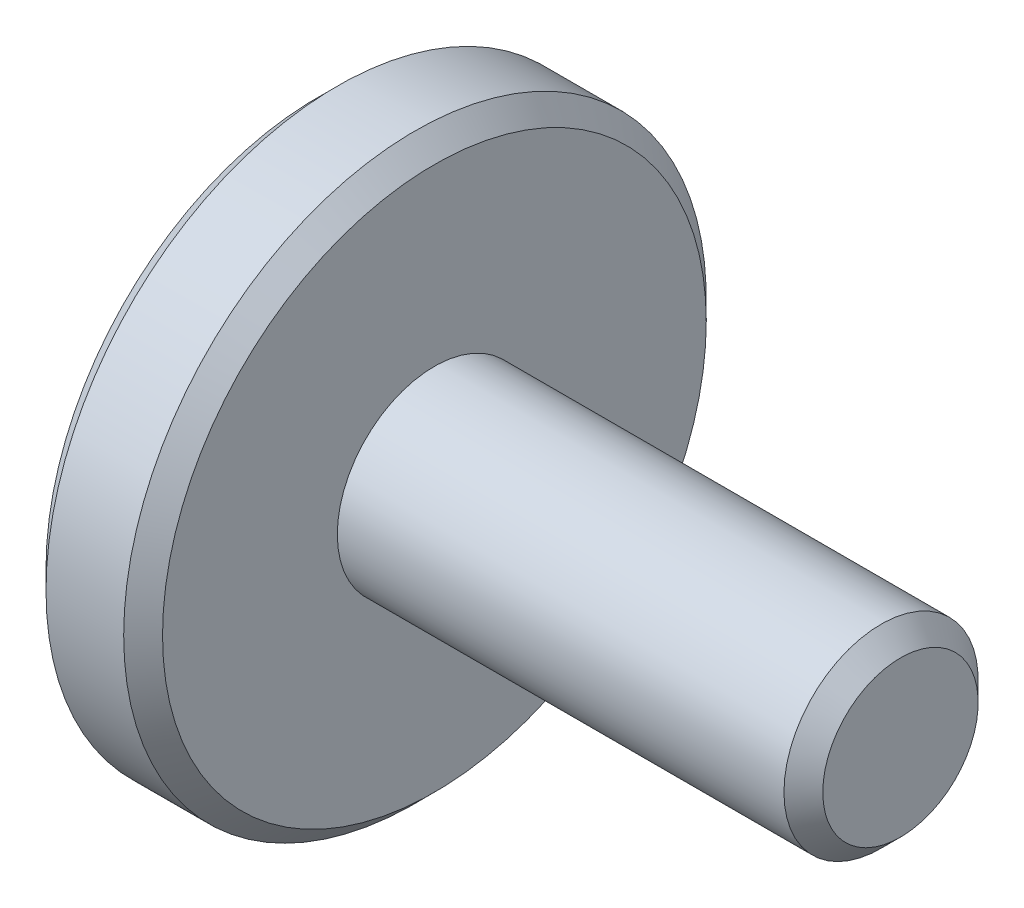
SolidWorks part; units mm, degrees
ref_plane "Plan de face" through (0, 0, 0) normal (0, 0, 1) x (1, 0, 0)
ref_plane "Plan de dessus" through (0, 0, 0) normal (0, 1, 0) x (1, 0, 0)
ref_plane "Plan de droite" through (0, 0, 0) normal (1, 0, 0) x (0, 0, -1)
sketch "Esquisse1" plane through (0, 0, 0) normal (0, 0, 1) x (1, 0, 0)
  line L0 (0, 0) -> (0, 7.5)
  line L1 (0, 7.5) -> (3, 7.5)
  line L2 (3, 7.5) -> (3, 2.5)
  line L3 (3, 2.5) -> (15, 2.5)
  line L4 (15, 2.5) -> (15, 0)
  line L5 (15, 0) -> (0, 0)
  line L6 (-65.1704, 0) -> (117.1561, 0) construction
  dimension "D1" = 5
  dimension "D2" = 12
  dimension "D3" = 3
  dimension "D4" = 15
revolve "Révolution1" add sketch "Esquisse1" angle 360 about L6
cosmetic thread "Représentation de filetage1" parameters "D2"=4.2
chamfer "Chanfrein1" distance 0.5 angle 45 3 edges at (0, 0, 7.5) (3, 0, 7.5) (15, 0, 2.5)
